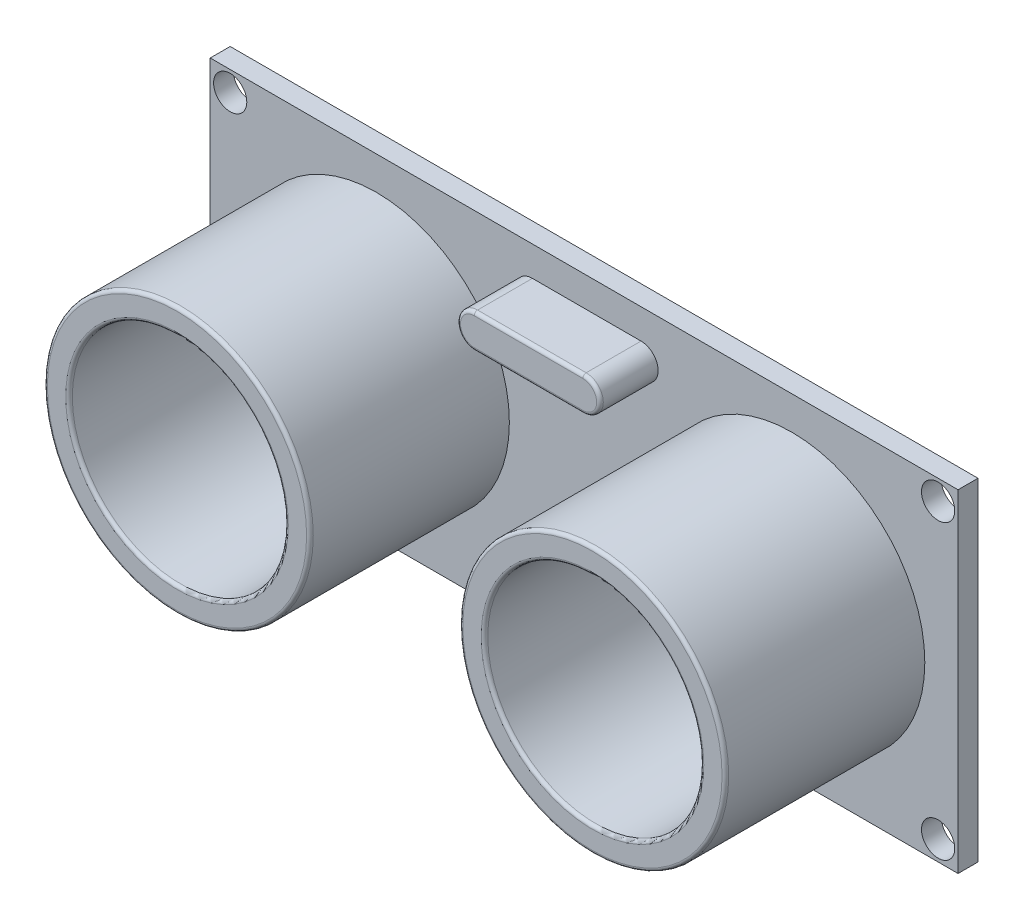
SolidWorks part; units mm, degrees
ref_plane "前视基准面" through (0, 0, 0) normal (0, 0, 1) x (1, 0, 0)
ref_plane "上视基准面" through (0, 0, 0) normal (0, 1, 0) x (1, 0, 0)
ref_plane "右视基准面" through (0, 0, 0) normal (1, 0, 0) x (0, 0, -1)
sketch "草图1" plane through (0, 0, 0) normal (0, 0, 1) x (1, 0, 0)
  line L1 (-29.9734, 13.6539) -> (15.0266, 13.6539)
  line L2 (-29.9734, 13.6539) -> (-29.9734, -6.3461)
  line L3 (-29.9734, -6.3461) -> (15.0266, -6.3461)
  line L4 (15.0266, 13.6539) -> (15.0266, -6.3461)
  circle A0 centre (-28.7734, 12.4539) radius 1
  circle A1 centre (-28.7734, -5.1461) radius 1
  circle A2 centre (13.8266, 12.4539) radius 1
  circle A3 centre (13.8266, -5.1461) radius 1
  dimension "D3" = 2
  dimension "D4" = 2
  dimension "D5" = 2
  dimension "D6" = 2
  dimension "D1" = 45
  dimension "D2" = 20
  dimension "D7" = 1.2
  dimension "D8" = 1.2
  dimension "D9" = 1.2
  dimension "D10" = 1.2
  dimension "D11" = 1.2
  dimension "D12" = 1.2
  dimension "D13" = 1.2
  dimension "D14" = 1.2
extrude "凸台-拉伸1" add sketch "草图1" along normal blind 1.2
sketch "草图2" plane through (0, 0, 1.2) normal (0, 0, 1) x (1, 0, 0)
  line L0 (-29.9734, 13.6539) -> (-29.9734, -6.3461) construction
  line L1 (-29.9734, -6.3461) -> (15.0266, -6.3461) construction
  line L3 (15.0266, 13.6539) -> (-29.9734, 13.6539) construction
  line L4 (15.0266, -6.3461) -> (15.0266, 13.6539) construction
  circle A0 centre (-19.9734, 3.6539) radius 8
  circle A1 centre (5.0266, 3.6539) radius 8
  circle A2 centre (-19.9734, 3.6539) radius 6.5
  circle A3 centre (5.0266, 3.6539) radius 6.5
  dimension "D3" = 16
  dimension "D4" = 16
  dimension "D7" = 13
  dimension "D8" = 13
  dimension "D1" = 10
  dimension "D2" = 10
  dimension "D5" = 10
  dimension "D6" = 10
extrude "凸台-拉伸2" add sketch "草图2" along normal blind 12
sketch "草图3" plane through (0, 0, 1.2) normal (0, 0, 1) x (1, 0, 0)
  line L1 (-10.5869, 11.8624) -> (-4.051, 11.8624)
  line L3 (-10.5869, 9.8038) -> (-4.051, 9.8038)
  arc A0 (-10.5869, 11.8624) -> (-10.5869, 9.8038) centre (-10.5869, 10.8331) ccw
  arc A1 (-4.051, 9.8038) -> (-4.051, 11.8624) centre (-4.051, 10.8331) ccw
extrude "凸台-拉伸3" add sketch "草图3" along normal blind 3.5
fillet "圆角1" radius 0.2 8 edges at (-7.319, 11.8624, 4.7) (-3.0218, 10.8331, 4.7) (-7.319, 9.8038, 4.7) (-11.6162, 10.8331, 4.7) (11.5266, 3.6539, 13.2) (13.0266, 3.6539, 13.2) (-13.4734, 3.6539, 13.2) (-11.9734, 3.6539, 13.2)
sketch "草图5" plane through (0, 0, 0) normal (0, 0, -1) x (-1, 0, 0)
  line L0 (-15.0266, -6.3461) -> (-15.0266, 13.6539) construction
  line L1 (1.9734, -3.3461) -> (12.4734, -3.3461)
  line L2 (1.9734, -3.3461) -> (1.9734, -5.8461)
  line L3 (1.9734, -5.8461) -> (12.4734, -5.8461)
  line L4 (12.4734, -3.3461) -> (12.4734, -5.8461)
  line L5 (-15.0266, 13.6539) -> (29.9734, 13.6539) construction
  dimension "D1" = 10.5
  dimension "D2" = 2.5
  dimension "D3" = 17
  dimension "D4" = 17
extrude "凸台-拉伸4" add sketch "草图5" along normal blind 2.5
fillet "圆角2" radius 0.8 4 edges at (-12.4734, -3.3461, -1.25) (-12.4734, -5.8461, -1.25) (-1.9734, -5.8461, -1.25) (-1.9734, -3.3461, -1.25)
sketch "草图7" plane through (0, 0, -2.5) normal (0, 0, -1) x (-1, 0, 0)
  line L2 (1.9734, -4.1461) -> (1.9734, -5.0461) construction
  circle A0 centre (4.1734, -4.7741) radius 0.4
  dimension "D2" = 0.8
  dimension "D3" = 2.2
ref_plane "基准面1" through (-4.1734, 0, 0) normal (1, 0, 0) x (0, 0, -1)
sketch "草图8" plane through (-4.1734, 0, 0) normal (1, 0, 0) x (0, 0, -1)
  line L0 (2.5, -4.7741) -> (4, -4.7741)
  line L1 (2.5, -5.1741) -> (2.5, -4.3741) construction
  line L2 (4.7458, -5.52) -> (4.7458, -12.52)
  arc A0 (4.7458, -5.52) -> (4, -4.7741) centre (4, -5.52) ccw
  dimension "D1" = 1.5
  dimension "D2" = 7
sweep "扫描1" add profiles "草图7" path "草图8"
pattern_linear "阵列(线性)1" count 4 spacing 2 along (-1, 0, 0) of "扫描1"
